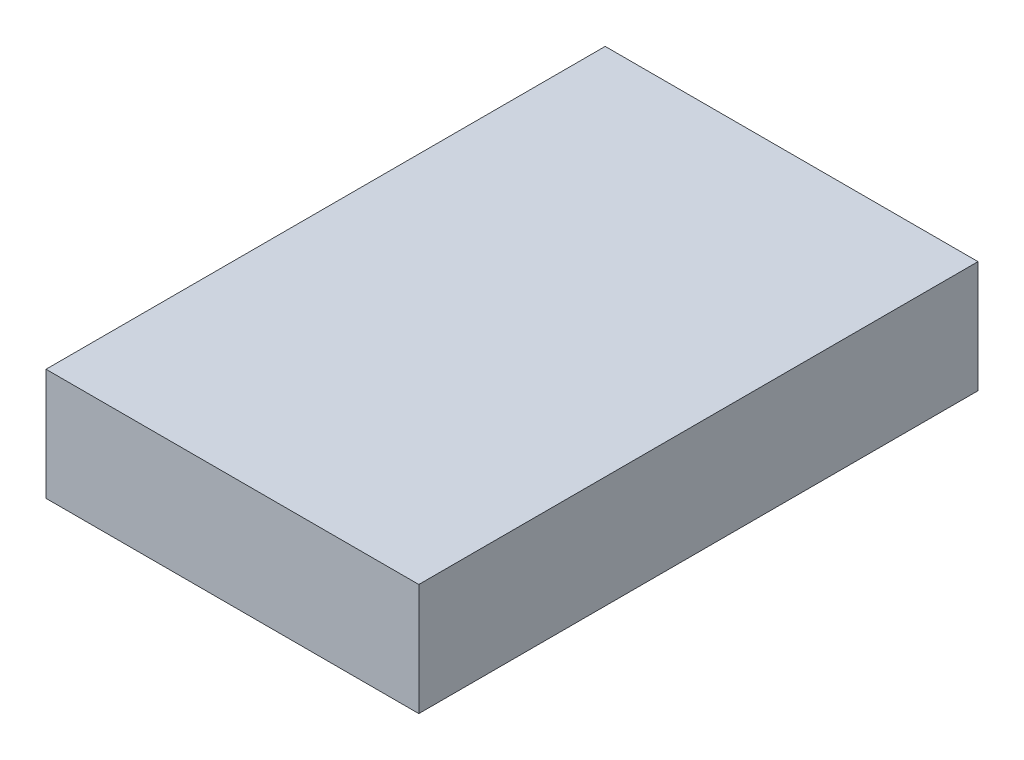
SolidWorks part; units mm, degrees
ref_plane "前视基准面" through (0, 0, 0) normal (0, 0, 1) x (1, 0, 0)
ref_plane "上视基准面" through (0, 0, 0) normal (0, 1, 0) x (1, 0, 0)
ref_plane "右视基准面" through (0, 0, 0) normal (1, 0, 0) x (0, 0, -1)
other "Configuration Table"
sketch "草图1" plane through (0, 0, 0) normal (0, 0, 1) x (1, 0, 0)
  line L0 (-5, 0) -> (5, 0)
extrude "Thin_3_0.001" add sketch "草图1" along normal blind 10 and the other way blind 5 thin
